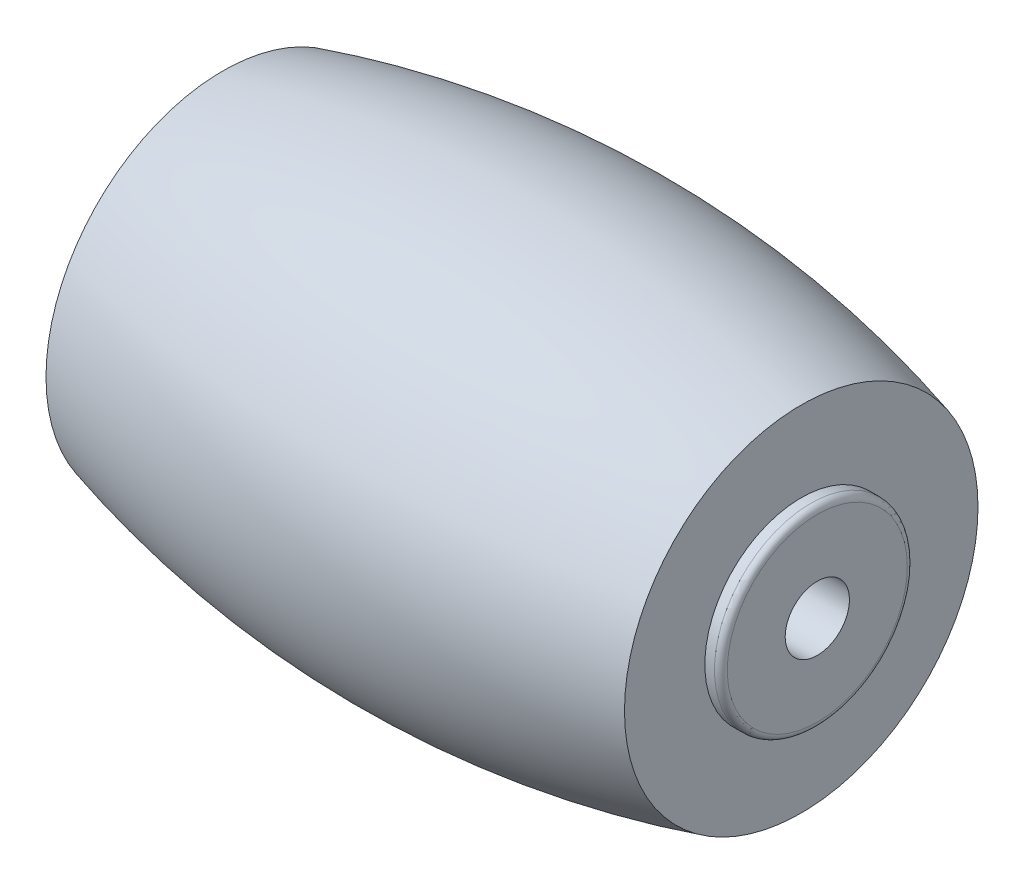
SolidWorks part; units mm, degrees
ref_plane "Front Plane" through (0, 0, 0) normal (0, 0, 1) x (1, 0, 0)
ref_plane "Top Plane" through (0, 0, 0) normal (0, 1, 0) x (1, 0, 0)
ref_plane "Right Plane" through (0, 0, 0) normal (1, 0, 0) x (0, 0, -1)
sketch "Sketch1" plane through (0, 0, 0) normal (0, 1, 0) x (1, 0, 0)
  line L0 (0, 0) -> (-202751.7478, 0) construction
  line L1 (0, 0) -> (0, -202751.7478) construction
  line L2 (0, 0) -> (-9, 0)
  line L3 (-9, 0) -> (-9, 5.5)
  line L4 (0, 0) -> (9, 0)
  line L5 (9, 0) -> (9, 5.5)
  arc A0 (-9, 5.5) -> (9, 5.5) centre (0, -26.7836) cw
  dimension "D1" = 9
  dimension "D2" = 5.5
revolve "Revolve1" add sketch "Sketch1" angle 360 about L0
sketch "Sketch3" plane through (9, 0, 0) normal (1, 0, 0) x (0, 0, -1)
  circle A0 centre (0, 0) radius 3
  dimension "D1" = 6
extrude "Boss-Extrude1" add sketch "Sketch3" along normal blind 0.5
ref_plane "Plane1" through (0, 0, 0) normal (1, 0, 0) x (0, 0, -1)
mirror "Mirror1" about plane through (0, 0, 0) normal (1, 0, 0) of "Boss-Extrude1"
sketch "Sketch4" plane through (-9.5, 0, 0) normal (-1, 0, 0) x (0, 0, 1)
  circle A0 centre (0, 0) radius 1
  dimension "D1" = 2
extrude "Cut-Extrude2" cut sketch "Sketch4" against normal through all
fillet "Fillet1" radius 0.2 2 edges at (9.5, 0, -3) (-9.5, 0, -3)
